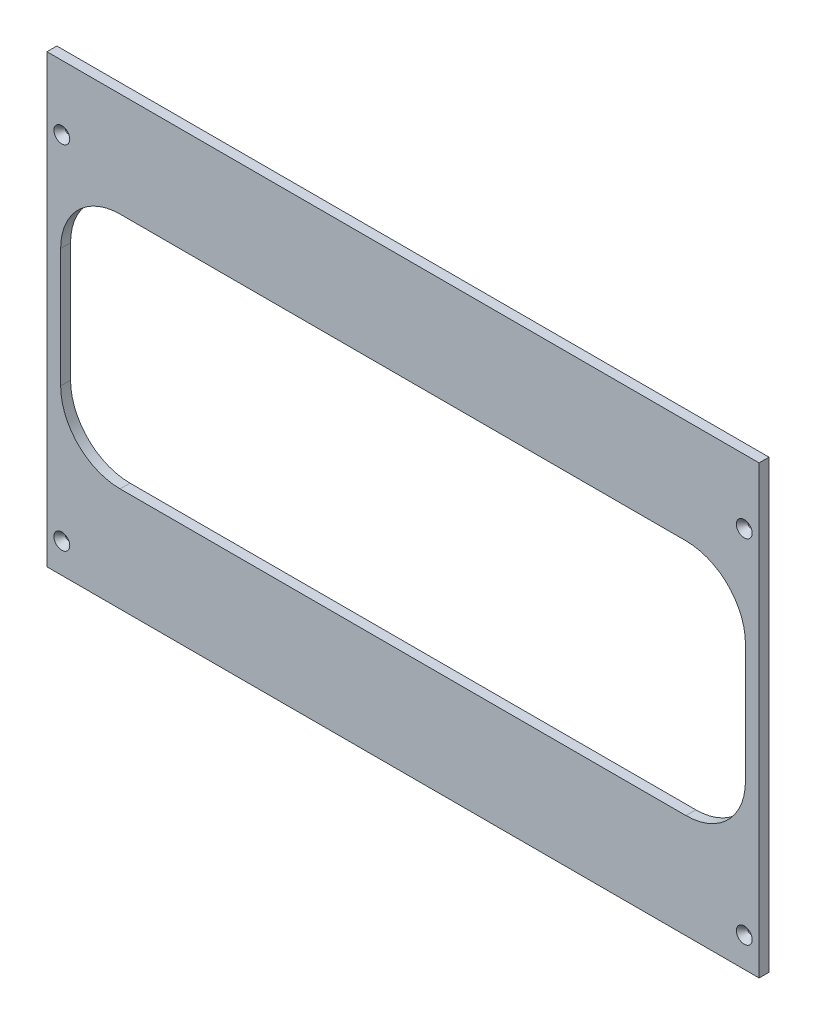
SolidWorks part; units mm, degrees
material "MDF"
ref_plane "Front Plane" through (0, 0, 0) normal (0, 0, 1) x (1, 0, 0)
ref_plane "Top Plane" through (0, 0, 0) normal (0, 1, 0) x (1, 0, 0)
ref_plane "Right Plane" through (0, 0, 0) normal (1, 0, 0) x (0, 0, -1)
sketch "Sketch1" plane through (0, 0, 0) normal (0, 0, 1) x (1, 0, 0)
  line L1 (-228.0888, 0) -> (228.0888, 0)
  line L2 (-228.0888, 0) -> (-228.0888, -285.75)
  line L3 (-228.0888, -285.75) -> (228.0888, -285.75)
  line L4 (228.0888, 0) -> (228.0888, -285.75)
  line L5 (58.5462, -285.75) -> (228.0888, -285.75) construction
  line L7 (228.0888, -3.175) -> (228.0888, -412.75) construction
  line L8 (228.0888, -412.75) -> (228.0888, -285.75) construction
  line L9 (-228.0888, -3.175) -> (-228.0888, -412.75) construction
  line L11 (-209.0388, 0) -> (-228.0888, 0) construction
extrude "Boss-Extrude1" add sketch "Sketch1" along normal blind 6.35
sketch "Sketch2" plane through (0, 0, 6.35) normal (0, 0, 1) x (1, 0, 0)
  line L0 (0, -285.75) -> (0, 0) construction
  line L1 (-228.0888, -285.75) -> (228.0888, -285.75) construction
  line L2 (228.0888, -285.75) -> (228.0888, 0) construction
  line L3 (-219.3258, -219.075) -> (219.3258, -219.075)
  line L4 (-219.3258, -219.075) -> (-219.3258, -66.675)
  line L5 (-219.3258, -66.675) -> (219.3258, -66.675)
  line L6 (219.3258, -219.075) -> (219.3258, -66.675)
  line L7 (-219.3258, -219.075) -> (219.3258, -66.675) construction
  line L8 (-219.3258, -66.675) -> (219.3258, -219.075) construction
  point P4 (0, -142.875)
  dimension "D1" = 8.763
  dimension "D2" = 152.4
extrude "Cut-Extrude1" cut sketch "Sketch2" against normal up to next
fillet "Fillet1" radius 38.1 4 edges at (219.3258, -66.675, 3.175) (219.3258, -219.075, 3.175) (-219.3258, -219.075, 3.175) (-219.3258, -66.675, 3.175)
hole_wizard "Hole1" positions "Sketch3" profile "Sketch4" legacy
sketch "Sketch3" plane through (0, 0, 6.35) normal (0, 0, 1) x (1, 0, 0)
  line L0 (-218.5638, -285.75) -> (-218.5638, -3.175) construction
  point P0 (-218.5638, -266.7)
  point P2 (-218.5638, -41.275)
  point P28 (218.5638, -266.7)
  point P29 (218.5638, -41.275)
sketch "Sketch4" plane through (-218.5638, -266.7, 6.35) normal (1, 0, 0) x (0, -1, 0)
  line L0 (0, 0) -> (0, 39.0539)
  line L1 (0, 39.0539) -> (1.5875, 38.1)
  line L2 (1.5875, 38.1) -> (1.5875, 4.0177)
  line L3 (1.5875, 4.0177) -> (5.08, 0)
  line L4 (5.08, 0) -> (0, 0)
  line L5 (0, -14.3089) -> (0, 102.4216) construction
  line L6 (0, 39.0539) -> (-1.5875, 38.1) construction
  line L7 (-1.5875, 4.0177) -> (-5.08, 0) construction
  dimension "Diameter" = 3.175
  dimension "Depth" = 38.1
  dimension "C-Sink Diameter" = 10.16
  dimension "C-Sink Angle" = 82
  dimension "Drill Angle" = 118
